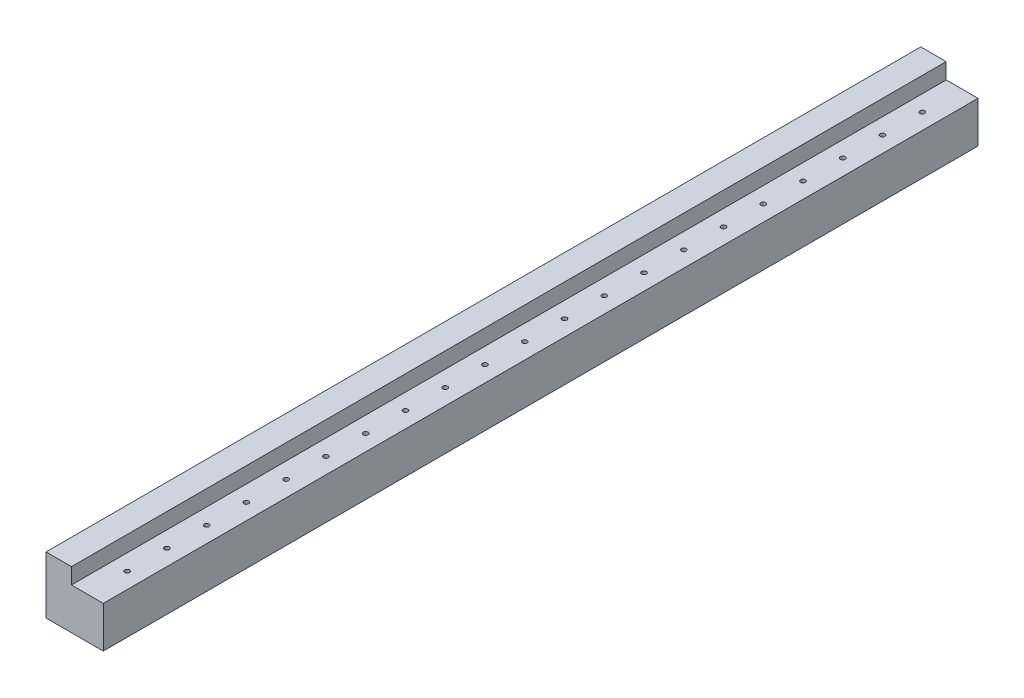
SolidWorks part; units mm, degrees
ref_plane "Plan de face" through (0, 0, 0) normal (0, 0, 1) x (1, 0, 0)
ref_plane "Plan de dessus" through (0, 0, 0) normal (0, 1, 0) x (1, 0, 0)
ref_plane "Plan de droite" through (0, 0, 0) normal (1, 0, 0) x (0, 0, -1)
sketch "Esquisse1" plane through (0, 0, 0) normal (0, 0, 1) x (1, 0, 0)
  line L1 (-18, 18) -> (18, 18)
  line L2 (-18, 18) -> (-18, -18)
  line L3 (-18, -18) -> (18, -18)
  line L4 (18, 18) -> (18, -18)
  line L5 (-18, 18) -> (18, -18) construction
  line L6 (-18, -18) -> (18, 18) construction
  point P0 (0, 0)
  dimension "D1" = 36
  dimension "D2" = 36
extrude "Boss.-Extru.1" add sketch "Esquisse1" along normal blind 550
sketch "Esquisse2" plane through (0, 0, 550) normal (0, 0, 1) x (1, 0, 0)
  line L1 (18, 18) -> (-2, 18)
  line L2 (18, 18) -> (18, 8)
  line L3 (18, 8) -> (-2, 8)
  line L4 (-2, 18) -> (-2, 8)
  dimension "D1" = 10
  dimension "D2" = 20
extrude "Enlèv. mat.-Extru.1" cut sketch "Esquisse2" against normal through all both and the other way through all
sketch "Esquisse3" plane through (0, 8, 0) normal (0, 1, 0) x (1, 0, 0)
  line L0 (-2, -550) -> (18, -550) construction
  line L1 (18, 0) -> (18, -550) construction
  circle A0 centre (8, -275) radius 1.5
  point P2 (0, 0)
  point P5 (8, -550)
  point P8 (18, -275)
  dimension "D1" = 3
extrude "Enlèv. mat.-Extru.2" cut sketch "Esquisse3" against normal blind 20
pattern_linear "Répétition linéaire1" count 11 spacing 25 along (0, 0, -1) count 11 spacing 25 along (0, 0, 1) of "Enlèv. mat.-Extru.2"
